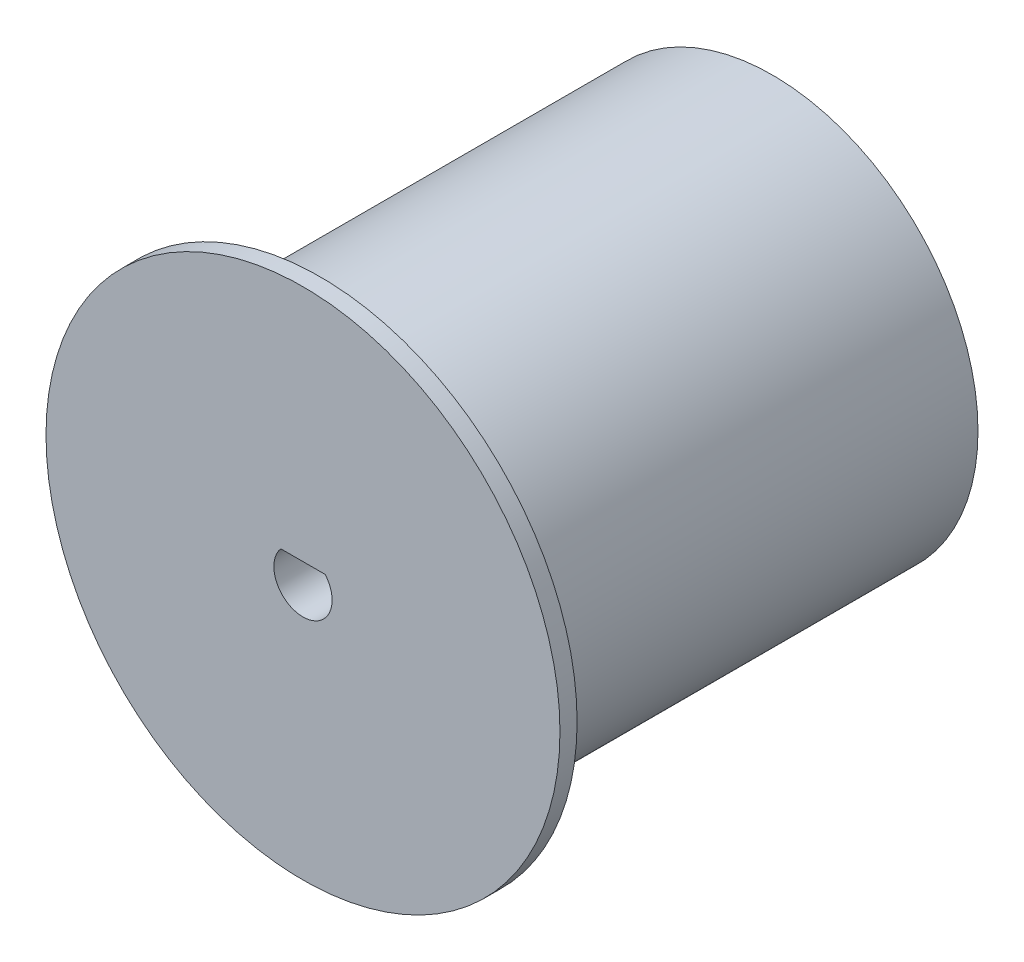
SolidWorks part; units mm, degrees
material "ABS"
ref_plane "Front" through (0, 0, 0) normal (0, 0, 1) x (1, 0, 0)
ref_plane "Top" through (0, 0, 0) normal (0, 1, 0) x (1, 0, 0)
ref_plane "Right" through (0, 0, 0) normal (1, 0, 0) x (0, 0, -1)
sketch "Эскиз1" plane through (0, 0, 0) normal (0, 1, 0) x (1, 0, 0)
  line L0 (0, 0) -> (0, 50.6994) construction
  line L1 (0, 0) -> (15, 0)
  line L2 (15, 0) -> (15, 1)
  line L3 (15, 1) -> (12, 1)
  line L4 (12, 1) -> (12, 27.4)
  line L5 (12, 27.4) -> (9.25, 27.4)
  line L6 (9.25, 27.4) -> (9.25, 7.4)
  line L7 (9.25, 7.4) -> (0, 7.4)
  line L8 (0, 0) -> (0, 7.4)
  dimension "D1" = 30
  dimension "D2" = 24
  dimension "D3" = 18.5
  dimension "D4" = 1
  dimension "D5" = 26.4
  dimension "D6" = 7.4
revolve "Повернуть1" add sketch "Эскиз1" angle 360 about L0
sketch "Эскиз2" plane through (0, 0, 0) normal (0, 0, 1) x (1, 0, 0)
  line L0 (-1.2, 0.9) -> (1.2, 0.9)
  line L1 (0, 0) -> (3.83, 0) construction
  line L2 (0, -1.5) -> (2.9377, -1.5) construction
  line L3 (-1.2961, 1.1) -> (1.2961, 1.1)
  arc A0 (-1.2, 0.9) -> (1.2, 0.9) centre (0, 0) ccw
  arc A1 (-1.2961, 1.1) -> (1.2961, 1.1) centre (0, 0) ccw
  dimension "D1" = 3
  dimension "D2" = 2.4
  dimension "D3" = 0.2
extrude "Вырез-Вытянуть1" cut sketch "Эскиз2" against normal blind 10 contours L0 A0 | L3 A1 A0 L0
